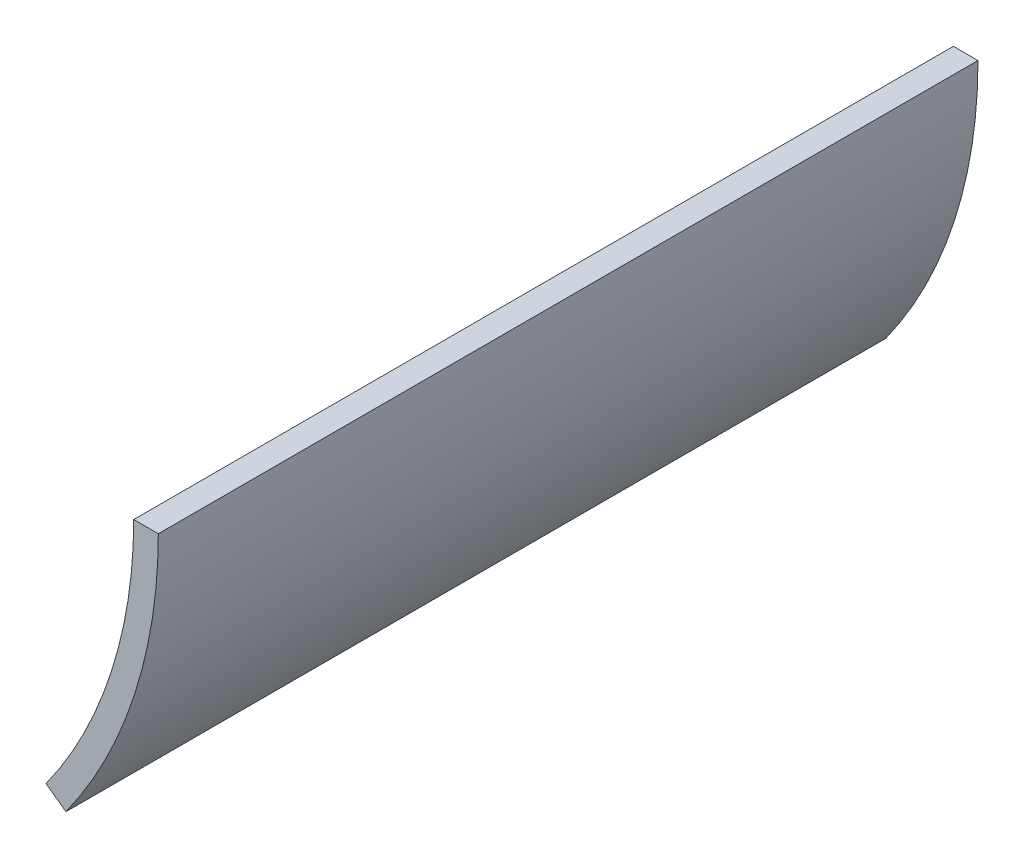
SolidWorks part; units mm, degrees
ref_plane "Front Plane" through (0, 0, 0) normal (0, 0, 1) x (1, 0, 0)
ref_plane "Top Plane" through (0, 0, 0) normal (0, 1, 0) x (1, 0, 0)
ref_plane "Right Plane" through (0, 0, 0) normal (1, 0, 0) x (0, 0, -1)
sketch "Sketch1" plane through (0, 0, 0) normal (0, 0, 1) x (1, 0, 0)
  line L0 (0, 0) -> (15, 0)
  line L1 (-41.3301, -175) -> (-53.5136, -166.25)
  arc A0 (15, 0) -> (-41.3301, -175) centre (-285, 0) cw
  arc A1 (-53.5136, -166.25) -> (0, 0) centre (-285, 0) ccw
  point P6 (-11.8218, -123.4305)
  dimension "D1" = 15
  dimension "D3" = 285
  dimension "D2" = 300
  dimension "D4" = 175
extrude "Boss-Extrude1" add sketch "Sketch1" along normal blind 500
